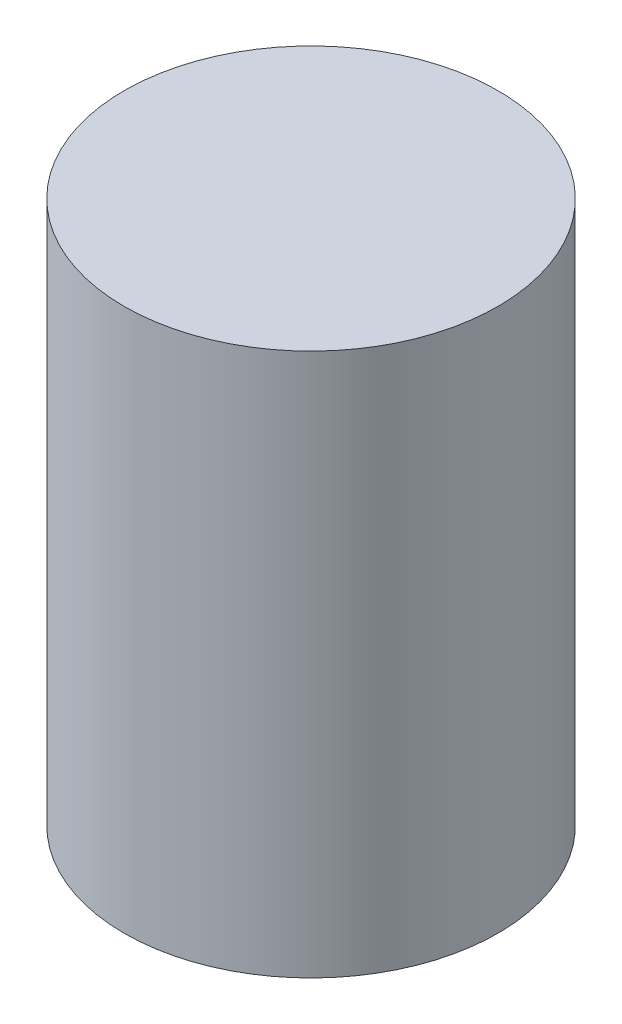
SolidWorks part; units mm, degrees
ref_plane "Front Plane" through (0, 0, 0) normal (0, 0, 1) x (1, 0, 0)
ref_plane "Top Plane" through (0, 0, 0) normal (0, 1, 0) x (1, 0, 0)
ref_plane "Right Plane" through (0, 0, 0) normal (1, 0, 0) x (0, 0, -1)
sketch "Sketch1" plane through (0, 0, 0) normal (0, 1, 0) x (1, 0, 0)
  circle A0 centre (0, 0) radius 5
  dimension "D1" = 10
extrude "Boss-Extrude1" add sketch "Sketch1" along normal mid plane 14.524
